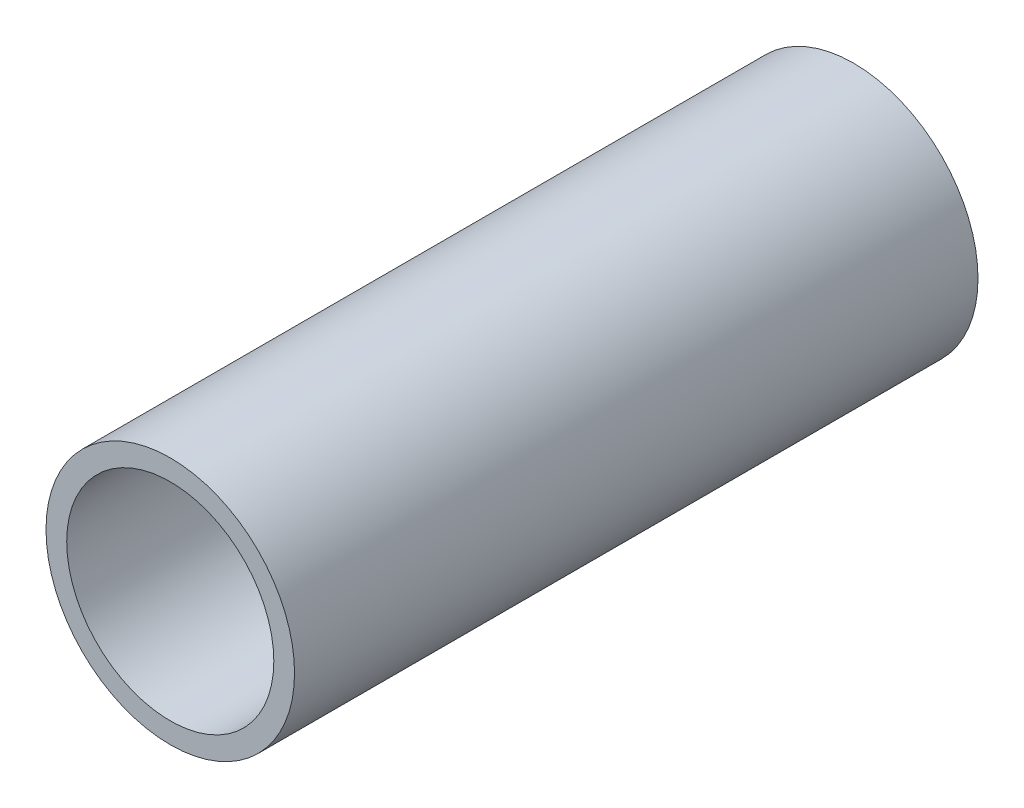
SolidWorks part; units mm, degrees
material "1023 Tôle d'acier au carbone (SS)"
ref_plane "Plan de face" through (0, 0, 0) normal (0, 0, 1) x (1, 0, 0)
ref_plane "Plan de dessus" through (0, 0, 0) normal (0, 1, 0) x (1, 0, 0)
ref_plane "Plan de droite" through (0, 0, 0) normal (1, 0, 0) x (0, 0, -1)
sketch "Esquisse1" plane through (0, 0, 0) normal (0, 0, 1) x (1, 0, 0)
  circle A0 centre (0, 0) radius 6
  circle A1 centre (0, 0) radius 5
  dimension "D1" = 12
  dimension "D2" = 1
extrude "Boss.-Extru.1" add sketch "Esquisse1" along normal blind 33
